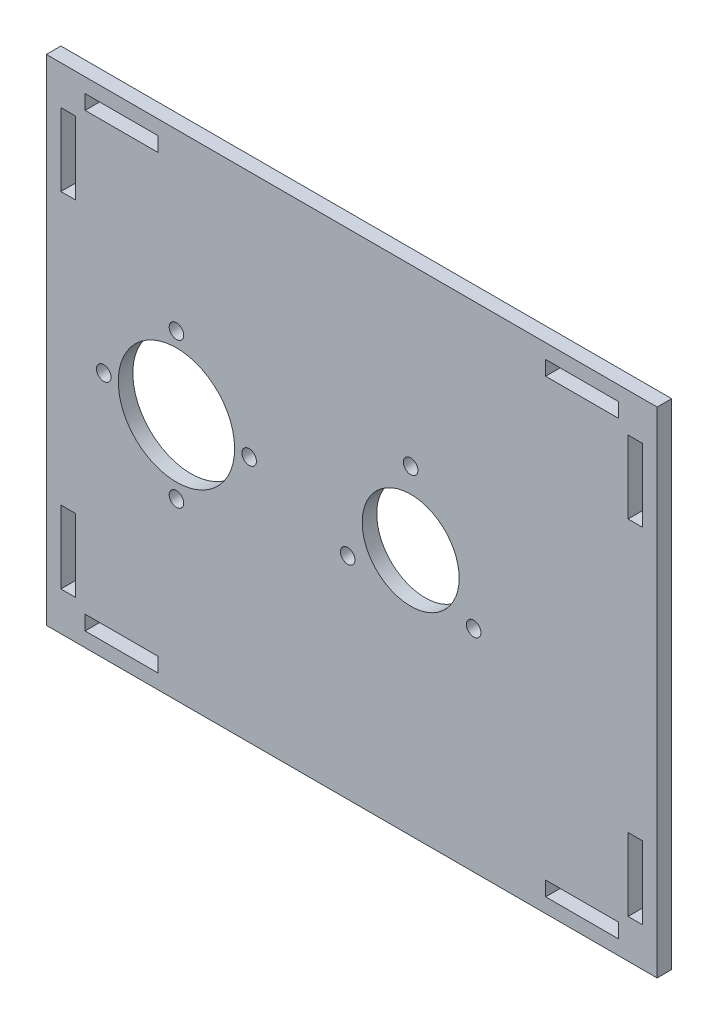
SolidWorks part; units mm, degrees
ref_plane "Front Plane" through (0, 0, 0) normal (0, 0, 1) x (1, 0, 0)
ref_plane "Top Plane" through (0, 0, 0) normal (0, 1, 0) x (1, 0, 0)
ref_plane "Right Plane" through (0, 0, 0) normal (1, 0, 0) x (0, 0, -1)
sketch "Sketch1" plane through (0, 0, 0) normal (0, 0, 1) x (1, 0, 0)
  line L0 (-48, -28) -> (-45, -28)
  line L1 (-51, 51) -> (75, 51)
  line L2 (-51, 51) -> (-51, -51)
  line L3 (-51, -51) -> (75, -51)
  line L4 (75, 51) -> (75, -51)
  line L5 (-48, 43) -> (-45, 43)
  line L6 (-48, 43) -> (-48, 28)
  line L7 (-48, 28) -> (-45, 28)
  line L8 (-45, 43) -> (-45, 28)
  line L9 (-48, 43) -> (-45, 28) construction
  line L10 (-48, 28) -> (-45, 43) construction
  line L11 (-48, -28) -> (-48, -43)
  line L12 (-48, -43) -> (-45, -43)
  line L13 (-45, -28) -> (-45, -43)
  line L14 (-48, -28) -> (-45, -43) construction
  line L15 (-48, -43) -> (-45, -28) construction
  line L16 (69, -28) -> (72, -28)
  line L17 (69, -28) -> (69, -43)
  line L18 (69, -43) -> (72, -43)
  line L19 (72, -28) -> (72, -43)
  line L20 (69, -28) -> (72, -43) construction
  line L21 (69, -43) -> (72, -28) construction
  line L22 (69, 43) -> (72, 43)
  line L23 (69, 43) -> (69, 28)
  line L24 (69, 28) -> (72, 28)
  line L25 (72, 43) -> (72, 28)
  line L26 (69, 43) -> (72, 28) construction
  line L27 (69, 28) -> (72, 43) construction
  line L29 (-43, 48) -> (-28, 48)
  line L30 (-43, 48) -> (-43, 45)
  line L31 (-43, 45) -> (-28, 45)
  line L32 (-28, 48) -> (-28, 45)
  line L33 (-43, 48) -> (-28, 45) construction
  line L34 (-43, 45) -> (-28, 48) construction
  line L35 (52, 48) -> (67, 48)
  line L36 (52, 48) -> (52, 45)
  line L37 (52, 45) -> (67, 45)
  line L38 (67, 48) -> (67, 45)
  line L39 (52, 48) -> (67, 45) construction
  line L40 (52, 45) -> (67, 48) construction
  line L41 (-43, -45) -> (-28, -45)
  line L42 (52, -45) -> (67, -45)
  line L43 (52, -45) -> (52, -48)
  line L44 (52, -48) -> (67, -48)
  line L45 (67, -45) -> (67, -48)
  line L46 (52, -45) -> (67, -48) construction
  line L47 (52, -48) -> (67, -45) construction
  line L48 (-43, -45) -> (-43, -48)
  line L49 (-43, -48) -> (-28, -48)
  line L50 (-28, -45) -> (-28, -48)
  line L51 (-43, -45) -> (-28, -48) construction
  line L52 (-43, -48) -> (-28, -45) construction
  circle A0 centre (-24.1573, 0) radius 12
  circle A1 centre (24.1573, 0) radius 10
  point P4 (-35.5, 46.5)
  point P6 (0, 0)
  point P15 (59.5, 46.5)
  point P18 (-46.5, 35.5)
  point P25 (-46.5, -35.5)
  point P30 (-35.5, -46.5)
  point P31 (59.5, -46.5)
  point P37 (70.5, -35.5)
  point P45 (70.5, 35.5)
  point P50 (0, 0)
  point P51 (0, 0)
  point P52 (0, 0)
  point P53 (0, 0)
  point P54 (0, 0)
  point P55 (0, 0)
  point P56 (0, 0)
  point P57 (0, 0)
  point P58 (0, 0)
  point P59 (0, 0)
  point P60 (0, 0)
  point P61 (0, 0)
  point P62 (0, 0)
  point P63 (0, 0)
  point P64 (0, 0)
  point P65 (0, 0)
  point P66 (0, 0)
extrude "Boss-Extrude1" add sketch "Sketch1" along normal blind 3
sketch "Sketch2" plane through (0, 0, 3) normal (0, 0, 1) x (1, 0, 0)
  circle A1 centre (24.1573, 15) radius 1.5
extrude "Cut-Extrude1" cut sketch "Sketch2" against normal blind 3
pattern_circular "CirPattern1" count 3 over 360 about axis through (24.1573, 0, 0) along (0, 0, 1) of "Cut-Extrude1"
sketch "Sketch3" plane through (0, 0, 3) normal (0, 0, 1) x (1, 0, 0)
  circle A1 centre (-24.1573, 15) radius 1.5
extrude "Cut-Extrude2" cut sketch "Sketch3" against normal blind 3
pattern_circular "CirPattern2" count 4 over 360 about axis through (-24.1573, 0, 0) along (0, 0, 1) of "Cut-Extrude2"
